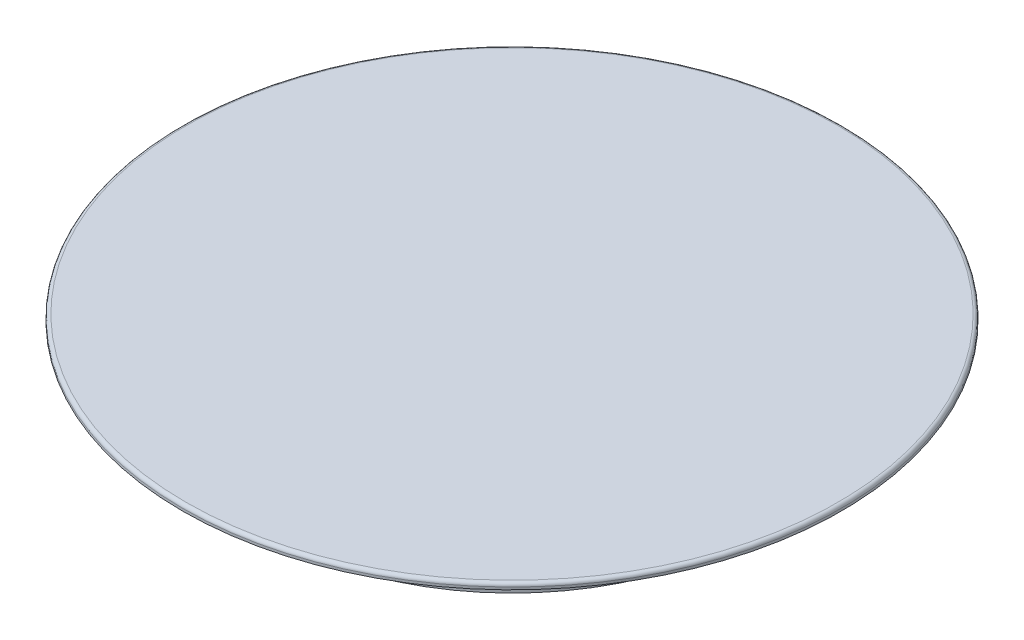
SolidWorks part; units mm, degrees
ref_plane "Front Plane" through (0, 0, 0) normal (0, 0, 1) x (1, 0, 0)
ref_plane "Top Plane" through (0, 0, 0) normal (0, 1, 0) x (1, 0, 0)
ref_plane "Right Plane" through (0, 0, 0) normal (1, 0, 0) x (0, 0, -1)
sketch "Sketch1" plane through (0, 0, 0) normal (0, 1, 0) x (1, 0, 0)
  circle A0 centre (0, 0) radius 95
  dimension "D1" = 190
extrude "Boss-Extrude1" add sketch "Sketch1" along normal blind 1.7
fillet "Fillet1" radius 1 1 edges at (0, 1.7, 95)
sketch "Sketch2" plane through (0, 0, 0) normal (0, -1, 0) x (1, 0, 0)
  circle A0 centre (0, 0) radius 70
  dimension "D1" = 140
extrude "Boss-Extrude2" add sketch "Sketch2" along normal blind 18.5
draft "Draft3" type of draft neutral plane draft angle 2 faces to draft 1 face at (0, -18.5, -70) neutral plane through (0, -18.5, 0) neutral plane normal (0, -1, 0) reverse direction yes parameters "D1"=2
